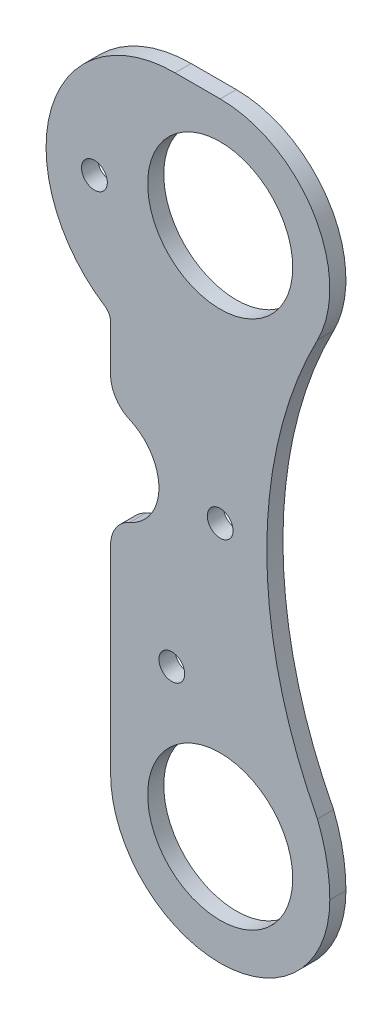
SolidWorks part; units mm, degrees
material "6061 Alloy"
ref_plane "Front Plane" through (0, 0, 0) normal (0, 0, 1) x (1, 0, 0)
ref_plane "Top Plane" through (0, 0, 0) normal (0, 1, 0) x (1, 0, 0)
ref_plane "Right Plane" through (0, 0, 0) normal (1, 0, 0) x (0, 0, -1)
sketch "Sketch1" plane through (0, 0, 0) normal (0, 0, 1) x (1, 0, 0)
  line L0 (0, 0) -> (0, -101.6) construction
  line L1 (21.59, -120.5575) -> (-21.59, -120.5575) construction
  line L2 (-8.89, 25.4) -> (8.89, 25.4)
  line L3 (-21.59, 12.7) -> (-21.59, -117.7751)
  line L5 (21.59, 12.7) -> (21.59, -117.7751)
  line L9 (-23.3829, -122.6853) -> (-33.2033, -134.3394)
  line L10 (-36.322, 25.4) -> (20.828, 25.4) construction
  line L11 (-36.322, 25.4) -> (-36.322, -203.2) construction
  line L12 (-36.322, -203.2) -> (20.828, -203.2) construction
  line L13 (20.828, 25.4) -> (20.828, -203.2) construction
  line L15 (-7.9527, -155.6168) -> (19.7971, -122.6853)
  line L16 (-32.4392, -143.2871) -> (-16.9004, -156.3809)
  circle A0 centre (0, 0) radius 38.1 construction
  circle A1 centre (0, -101.6) radius 38.1 construction
  circle A2 centre (0, 0) radius 14.2875
  circle A3 centre (0, -101.6) radius 14.2875
  arc A6 (8.89, 25.4) -> (21.59, 12.7) centre (8.89, 12.7) cw
  arc A7 (-8.89, 25.4) -> (-21.59, 12.7) centre (-8.89, 12.7) ccw
  circle A10 centre (-18.5321, -142.5501) radius 2.54
  arc A13 (-23.3829, -122.6853) -> (-21.59, -117.7751) centre (-29.21, -117.7751) ccw
  arc A14 (19.7971, -122.6853) -> (21.59, -117.7751) centre (13.97, -117.7751) ccw
  arc A15 (-16.9004, -156.3809) -> (-7.9527, -155.6168) centre (-12.8086, -151.525) ccw
  arc A16 (-33.2033, -134.3394) -> (-32.4392, -143.2871) centre (-28.3474, -138.4312) ccw
  circle A17 centre (0, -50.8) radius 2.54
  point P13 (-192.705, 39.2708)
  point P20 (21.59, 25.4)
  point P23 (-21.59, 25.4)
  point P31 (-36.322, -138.0404)
  dimension "D2" = 76.2
  dimension "D3" = 76.2
  dimension "D4" = 28.575
  dimension "D5" = 28.575
  dimension "D10" = 228.6
  dimension "D11" = 36.322
  dimension "D13" = 5.08
  dimension "D19" = 6.35
  dimension "D20" = 7.62
  dimension "D21" = 12.7
  dimension "D22" = 5.08
  dimension "D1" = 101.6
  dimension "D6" = 43.18
  dimension "D7" = 21.59
  dimension "D8" = 25.4
  dimension "D9" = 57.15
  dimension "D12" = 25.4
  dimension "D14" = 33.02
  dimension "D15" = 16.51
  dimension "D16" = 21.59
  dimension "D17" = 9.525
  dimension "D18" = 18.9575
extrude "Boss-Extrude1" add sketch "Sketch1" along normal blind 3.175
sketch "Sketch2" plane through (0, 0, 0) normal (0, 0, 1) x (1, 0, 0)
  line L0 (-21.59, -41.275) -> (-21.59, -60.325)
  line L1 (0, 0) -> (0, -101.6) construction
  line L4 (21.59, -117.7751) -> (21.59, 12.7) construction
  line L5 (-21.59, -50.8) -> (97.79, -50.8) construction
  line L6 (-21.59, 12.7) -> (-21.59, -117.7751) construction
  line L7 (0, 0) -> (-39.9512, 0) construction
  line L9 (16.51, -115.5122) -> (-17.5013, -155.8745)
  line L10 (-32.4392, -143.2871) -> (-16.9004, -156.3809) construction
  line L11 (-7.9527, -155.6168) -> (19.7971, -122.6853) construction
  line L13 (27.94, -121.6567) -> (-7.7896, -164.0581)
  line L14 (-7.7896, -164.0581) -> (-17.5013, -155.8745)
  line L15 (27.94, -121.6567) -> (27.94, 0)
  line L16 (27.94, 0) -> (21.59, 0)
  arc A1 (19.1591, -91.6472) -> (19.1591, -9.9528) centre (97.79, -50.8) cw
  arc A2 (-21.59, -60.325) -> (-21.59, -41.275) centre (-21.59, -50.8) ccw
  arc A3 (21.59, 0) -> (19.1591, -9.9528) centre (0, 0) cw
  arc A4 (21.59, -101.6) -> (19.1591, -91.6472) centre (0, -101.6) ccw
  arc A5 (21.59, -101.6) -> (16.51, -115.5122) centre (0, -101.6) cw
  dimension "D2" = 12.7
  dimension "D3" = 50.8
  dimension "D4" = 6.35
  dimension "D1" = 76.2
  dimension "D5" = 19.05
extrude "Cut-Extrude1" cut sketch "Sketch2" along normal through all contours A1 A3 L16 L15 L13 L14 L9 A5 A4 | L0 A2
sketch "Sketch3" plane through (0, 0, 3.175) normal (0, 0, 1) x (1, 0, 0)
  line L0 (-27.3514, -127.3948) -> (-36.0255, -137.6886)
  line L3 (-27.3514, -127.3948) -> (-7.5576, -144.074)
  line L4 (-23.3829, -122.6853) -> (-33.2033, -134.3394) construction
  line L5 (16.51, -115.5122) -> (-17.5013, -155.8745) construction
  line L7 (-35.4064, -144.9387) -> (-24.4031, -154.2106)
  line L8 (-23.3829, -122.6853) -> (-33.2033, -134.3394) construction
  line L9 (-7.5576, -144.074) -> (-15.4554, -153.4465)
  line L10 (-32.4392, -143.2871) -> (-17.5013, -155.8745) construction
  circle A2 centre (-18.5321, -142.5501) radius 2.54
  circle A3 centre (-18.5321, -142.5501) radius 2.54 construction
  arc A5 (-36.0255, -137.6886) -> (-35.4064, -144.9387) centre (-32.0909, -141.0041) ccw
  arc A6 (-24.4031, -154.2106) -> (-15.4554, -153.4465) centre (-20.3113, -149.3547) ccw
  dimension "D2" = 6.35
  dimension "D3" = 5.1453
  dimension "D1" = 3.175
fillet "Fillet3" radius 6.35 2 edges at (-21.59, -60.325, 1.5875) (-21.59, -41.275, 1.5875)
extrude "Boss-Extrude3" add sketch "Sketch3" against normal blind 3.175
sketch "Sketch6" plane through (0, 0, 3.175) normal (0, 0, 1) x (1, 0, 0)
  line L0 (-35.4064, -144.9387) -> (-63.6204, -121.1641)
  line L1 (-63.6204, -121.1641) -> (-51.345, -106.5965)
  line L2 (-51.345, -106.5965) -> (-27.0656, -127.0555)
  line L4 (-35.4064, -144.9387) -> (-24.4031, -154.2106) construction
  line L5 (-23.3829, -122.6853) -> (-36.0255, -137.6886) construction
  line L6 (-35.4064, -144.9387) -> (-27.0656, -127.0555)
  circle A0 centre (-52.6268, -117.9721) radius 2.54
  dimension "D4" = 5.08
  dimension "D1" = 31.75
  dimension "D2" = 9.525
  dimension "1" = 19.05
  dimension "D3" = 6.35
extrude "Boss-Extrude4" add sketch "Sketch6" against normal blind 3.175
fillet "Fillet2" radius 6.35 3 edges at (-63.6204, -121.1641, 1.5875) (-51.345, -106.5965, 1.5875) (-27.0656, -127.0555, 1.5875)
sketch "Sketch7" plane through (0, 0, 3.175) normal (0, 0, 1) x (1, 0, 0)
  line L0 (-21.59, 12.7) -> (-21.59, -36.2503) construction
  line L1 (21.59, 0) -> (21.59, 12.7) construction
  line L2 (-21.59, 0) -> (21.59, 0) construction
  line L3 (-21.59, 0) -> (-21.59, 31.75)
  line L4 (-21.59, 31.75) -> (21.59, 31.75)
  line L5 (21.59, 31.75) -> (21.59, 0)
  line L6 (8.89, 25.4) -> (-8.89, 25.4) construction
  arc A0 (-21.59, 0) -> (21.59, 0) centre (0, 0) cw
  dimension "D1" = 6.35
extrude "Cut-Extrude2" cut sketch "Sketch7" against normal through all
sketch "Sketch10" plane through (0, 0, 3.175) normal (0, 0, 1) x (1, 0, 0)
  line L0 (16.51, -115.5122) -> (-17.5013, -155.8745) construction
  line L1 (-18.1519, -155.3263) -> (-17.3615, -157.512)
  line L2 (-17.3615, -157.512) -> (-14.3757, -156.4323)
  line L3 (-14.3757, -156.4323) -> (-15.4554, -153.4465)
  line L5 (-18.1519, -155.3263) -> (-17.5013, -155.8745) construction
  circle A0 centre (-20.3113, -149.3547) radius 6.35 construction
  arc A1 (-24.4031, -154.2106) -> (-18.1519, -155.3263) centre (-20.3113, -149.3547) ccw construction
  arc A2 (-18.1519, -155.3263) -> (-15.4554, -153.4465) centre (-20.3113, -149.3547) ccw
  dimension "D1" = 3.175
  dimension "D2" = 30
extrude "Cut-Extrude3" cut sketch "Sketch10" against normal through all
sketch "Sketch12" plane through (0, 0, 3.175) normal (0, 0, 1) x (1, 0, 0)
  line L0 (-21.59, -65.3497) -> (-21.59, -117.7751) construction
  line L1 (-21.59, -101.6) -> (-72.39, -101.6)
  line L2 (-72.39, -101.6) -> (-72.39, -165.1)
  line L3 (-72.39, -165.1) -> (16.51, -165.1)
  line L4 (16.51, -165.1) -> (16.51, -115.5122)
  arc A2 (16.51, -115.5122) -> (-21.59, -101.6) centre (0, -101.6) cw
  dimension "D1" = 63.5
  dimension "D2" = 88.9
extrude "Cut-Extrude4" cut sketch "Sketch12" against normal through all
sketch "Sketch15" plane through (0, 0, 3.175) normal (0, 0, 1) x (1, 0, 0)
  line L0 (-21.59, 0) -> (-21.59, -36.2503) construction
  line L5 (-21.59, -29.21) -> (-21.59, 0)
  line L7 (0, 21.59) -> (-16.6076, 6.9565)
  line L8 (-16.6076, 6.9565) -> (-12.5785, -28.9408)
  line L9 (-8.89, 21.59) -> (0, 21.59)
  arc A0 (-12.5785, -28.9408) -> (-34.29, -3.81) centre (-8.89, -3.81) cw
  arc A1 (-8.89, 21.59) -> (-34.29, -3.81) centre (-8.89, -3.81) ccw
  circle A2 centre (-24.765, -3.81) radius 2.54
  arc A3 (19.1591, -9.9528) -> (-21.59, 0) centre (0, 0) ccw construction
  arc M10 (19.1591, -9.9528) -> (-21.59, 0) centre (0, 0) ccw
  line M11 (-21.59, 0) -> (-21.59, -36.2503)
  dimension "D1" = 12.7
  dimension "D4" = 3.175
  dimension "D3" = 5.08
  dimension "D2" = 25.4
extrude "Boss-Extrude8" add sketch "Sketch15" against normal blind 3.175 contours L9 A1 A0 A2 M11 M10
fillet "Fillet4" radius 2.54 1 edges at (-21.59, -25.807, 1.5875)
sketch "Sketch16" plane through (0, 0, 3.175) normal (0, 0, 1) x (1, 0, 0)
  line L1 (0, -102.5377) -> (0, -93.0735) construction
  line L2 (0, -101.6) -> (-11.1927, -101.6) construction
  line L4 (-21.59, -101.6) -> (-1.4895, -121.7005)
  line L5 (-1.4895, -121.7005) -> (4.5179, -121.7005)
  line L6 (4.5179, -121.7005) -> (21.59, -101.6)
  line L7 (-21.59, -65.3497) -> (-21.59, -101.6) construction
  line L8 (-21.59, -101.6) -> (-21.59, -104.2391)
  line L9 (21.59, -101.6) -> (21.59, -104.2391)
  arc A0 (-21.59, -104.2391) -> (21.59, -104.2391) centre (0, -104.2391) ccw
  arc A1 (-21.59, -101.6) -> (19.1591, -91.6472) centre (0, -101.6) ccw construction
  dimension "D1" = 2.6391
extrude "Boss-Extrude9" add sketch "Sketch16" against normal through all contours L6 L9 A0 L8 L4 L5
sketch "Sketch17" plane through (0, 0, 3.175) normal (0, 0, 1) x (1, 0, 0)
  circle A0 centre (0, -101.6) radius 14.2875
  circle A1 centre (0, -101.6) radius 14.2875 construction
extrude "Boss-Extrude10" add sketch "Sketch17" against normal through all
sketch "Sketch19" plane through (0, 0, 3.175) normal (0, 0, 1) x (1, 0, 0)
  line L0 (21.59, -104.2391) -> (21.59, -95.9079) construction
  line L1 (19.1591, -91.6472) -> (21.59, -91.6472)
  line L2 (21.59, -91.6472) -> (21.59, -104.2391)
  arc A0 (19.1591, -91.6472) -> (21.59, -104.2391) centre (-12.2375, -104.2391) cw
extrude "Cut-Extrude5" cut sketch "Sketch19" against normal through all
sketch "Sketch20" plane through (0, 0, 3.175) normal (0, 0, 1) x (1, 0, 0)
  circle A0 centre (0, -104.2391) radius 14.2875
  arc A1 (-21.59, -104.2391) -> (21.59, -104.2391) centre (0, -104.2391) ccw construction
  dimension "D1" = 28.575
extrude "Cut-Extrude6" cut sketch "Sketch20" against normal through all
sketch "Sketch21" plane through (0, 0, 3.175) normal (0, 0, 1) x (1, 0, 0)
  circle A0 centre (-9.525, -80.01) radius 2.54
  circle A1 centre (0, -50.8) radius 2.54 construction
  dimension "D1" = 29.21
  dimension "D2" = 9.525
extrude "Cut-Extrude7" cut sketch "Sketch21" against normal through all
